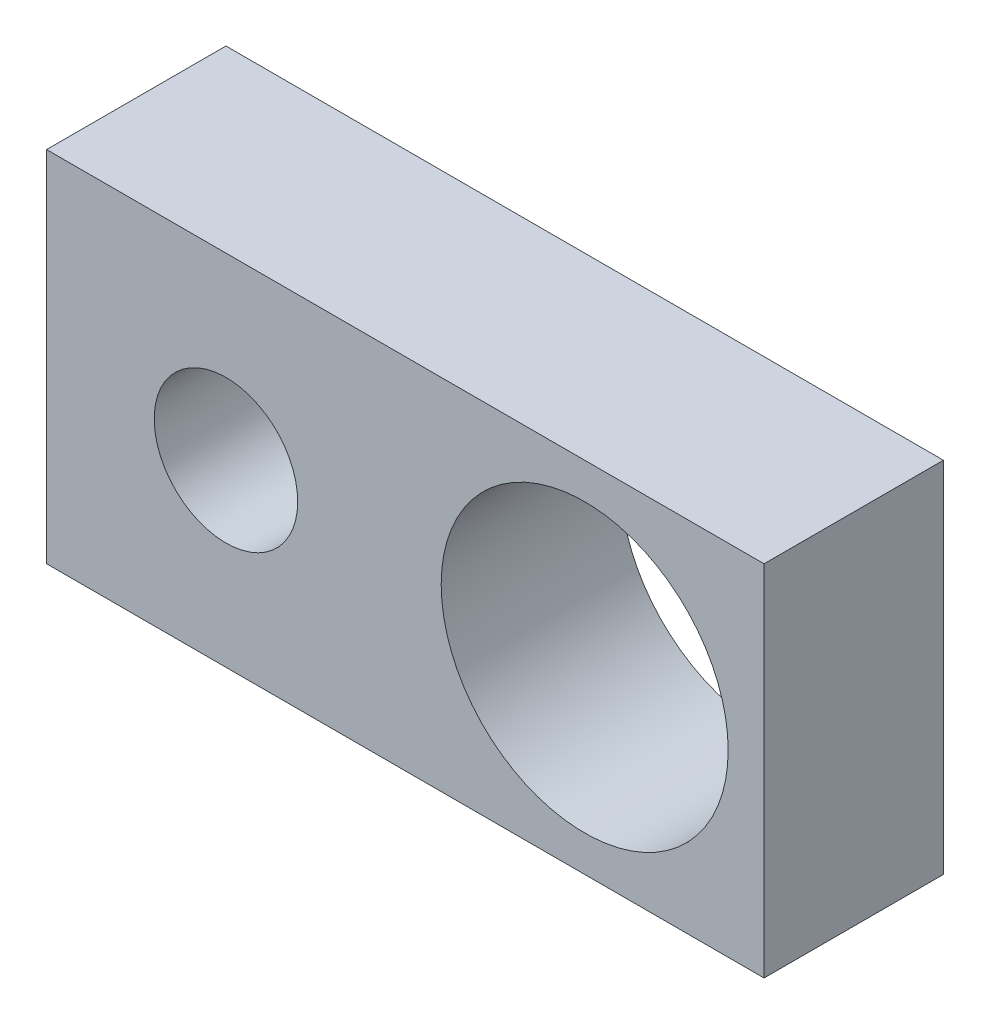
SolidWorks part; units mm, degrees
ref_plane "Plan de face" through (0, 0, 0) normal (0, 0, 1) x (1, 0, 0)
ref_plane "Plan de dessus" through (0, 0, 0) normal (0, 1, 0) x (1, 0, 0)
ref_plane "Plan de droite" through (0, 0, 0) normal (1, 0, 0) x (0, 0, -1)
sketch "Esquisse1" plane through (0, 0, 0) normal (0, 0, 1) x (1, 0, 0)
  line L0 (-21.7901, 0) -> (22.8385, 0) construction
  line L1 (20, -10) -> (-20, -10)
  line L2 (20, -10) -> (20, 10)
  line L3 (20, 10) -> (-20, 10)
  line L4 (-20, -10) -> (-20, 10)
  line L5 (20, -10) -> (-20, 10) construction
  line L6 (20, 10) -> (-20, -10) construction
  circle A0 centre (-10, 0) radius 4
  circle A1 centre (10, 0) radius 8
  point P0 (0, 0)
  dimension "D3" = 8
  dimension "D4" = 16
  dimension "D1" = 40
  dimension "D2" = 20
  dimension "D5" = 20
  dimension "D6" = 10
extrude "Boss.-Extru.1" add sketch "Esquisse1" along normal blind 10
